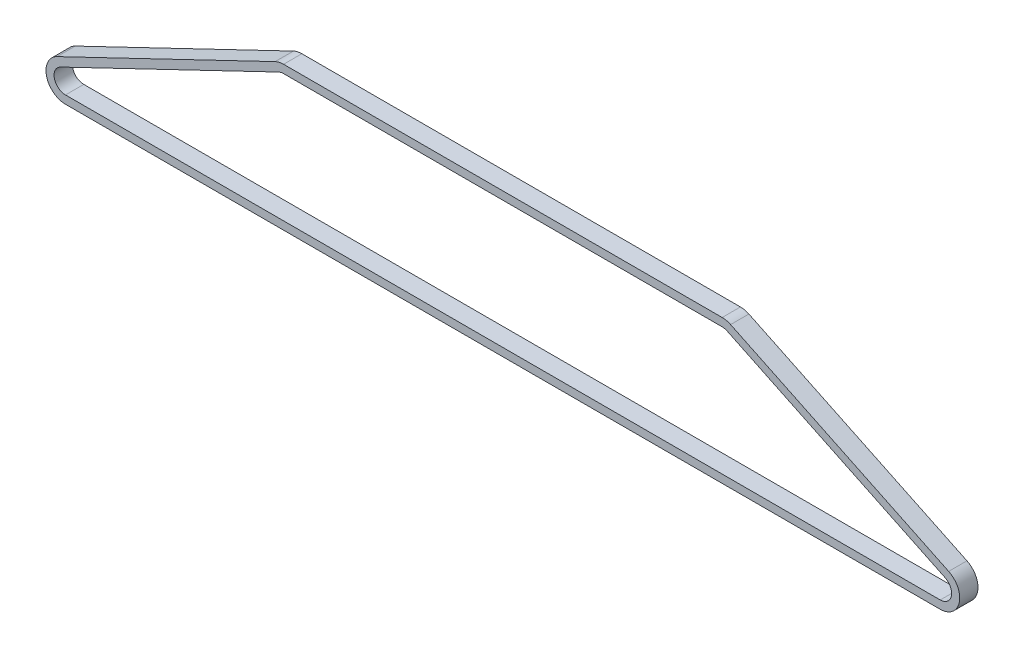
SolidWorks part; units mm, degrees
material "Rubber"
ref_plane "Front Plane" through (0, 0, 0) normal (0, 0, 1) x (1, 0, 0)
ref_plane "Top Plane" through (0, 0, 0) normal (0, 1, 0) x (1, 0, 0)
ref_plane "Right Plane" through (0, 0, 0) normal (1, 0, 0) x (0, 0, -1)
sketch "Sketch1" plane through (0, 0, 0) normal (0, 0, 1) x (1, 0, 0)
  line L0 (-72, 0) -> (0, 0) construction
  line L1 (-72, 1.872) -> (0, 1.872)
  line L2 (-107.8, -17.1867) -> (-72, 0) construction
  line L3 (-108.6102, -15.4991) -> (-72.8102, 1.6876)
  line L5 (-71.5739, -1.872) -> (-0.4261, -1.872)
  line L6 (-107.8, -17.1867) -> (35.8, -17.1867) construction
  line L8 (-107.8, -19.0587) -> (35.8, -19.0587)
  line L9 (-99.5752, -15.3147) -> (-71.5739, -1.872)
  line L10 (-99.5752, -15.3147) -> (27.5752, -15.3147)
  line L11 (0, 0) -> (35.8, -17.1867) construction
  line L12 (0.8102, 1.6876) -> (36.6102, -15.4991)
  line L13 (-0.4261, -1.872) -> (27.5752, -15.3147)
  line L14 (-72, 0) -> (0, 0) construction
  line L15 (-72, 3.2) -> (0, 3.2)
  line L16 (-71.2717, -3.2) -> (-0.7283, -3.2)
  line L17 (35.8, -17.1867) -> (0, 0) construction
  line L18 (21.7405, -13.9867) -> (-0.7283, -3.2)
  line L19 (37.1849, -14.3019) -> (1.3849, 2.8848)
  line L20 (35.8, -17.1867) -> (-107.8, -17.1867) construction
  line L21 (35.8, -20.3867) -> (-107.8, -20.3867)
  line L22 (33.4598, -13.9867) -> (24.8089, -13.9867)
  line L23 (-107.8, -17.1867) -> (-72, 0) construction
  line L24 (-109.1849, -14.3019) -> (-73.3849, 2.8848)
  line L25 (-93.7405, -13.9867) -> (-71.2717, -3.2)
  line L26 (21.7405, -13.9867) -> (-93.7405, -13.9867)
  circle A0 centre (35.8, -17.1867) radius 1.872 construction
  arc A1 (-72, 3.2) -> (-73.3849, 2.8848) centre (-72, 0) ccw
  arc A2 (35.8, -19.0587) -> (36.6102, -15.4991) centre (35.8, -17.1867) ccw
  circle A4 centre (-72, 0) radius 9.25 construction
  circle A6 centre (-72, 0) radius 9.25 construction
  circle A8 centre (-107.8, -17.1867) radius 1.872 construction
  arc A9 (-108.6102, -15.4991) -> (-107.8, -19.0587) centre (-107.8, -17.1867) ccw
  circle A10 centre (-107.8, -17.1867) radius 3.2 construction
  arc A11 (-109.1849, -14.3019) -> (-107.8, -20.3867) centre (-107.8, -17.1867) ccw
  arc A12 (-108.6102, -15.4991) -> (-107.8, -19.0587) centre (-107.8, -17.1867) ccw
  arc A14 (-72, 1.872) -> (-72.8102, 1.6876) centre (-72, 0) ccw
  arc A16 (-108.6102, -15.4991) -> (-107.8, -19.0587) centre (-107.8, -17.1867) ccw
  arc A17 (35.8, -19.0587) -> (36.6102, -15.4991) centre (35.8, -17.1867) ccw
  arc A18 (-72, 1.872) -> (-72.8102, 1.6876) centre (-72, 0) ccw
  arc A19 (0.8102, 1.6876) -> (0, 1.872) centre (0, 0) ccw
  arc A20 (35.8, -19.0587) -> (36.6102, -15.4991) centre (35.8, -17.1867) ccw
  arc A21 (0.8102, 1.6876) -> (0, 1.872) centre (0, 0) ccw
  arc A22 (1.3849, 2.8848) -> (0, 3.2) centre (0, 0) ccw
  arc A23 (35.8, -20.3867) -> (37.1849, -14.3019) centre (35.8, -17.1867) ccw
  arc A24 (1.3849, 2.8848) -> (0, 3.2) centre (0, 0) ccw
  arc A25 (35.8, -20.3867) -> (37.1849, -14.3019) centre (35.8, -17.1867) ccw
  arc A26 (-109.1849, -14.3019) -> (-107.8, -20.3867) centre (-107.8, -17.1867) ccw
  arc A27 (-109.1849, -14.3019) -> (-107.8, -20.3867) centre (-107.8, -17.1867) ccw
  arc A28 (-72.0041, -3.2) -> (-72, -3.2) centre (-72, 0) ccw
  arc A29 (-72, 3.2) -> (-73.3849, 2.8848) centre (-72, 0) ccw
  arc A30 (-72.0041, -3.2) -> (-72, -3.2) centre (-72, 0) ccw
  point P4 (-36, 0)
  point P7 (-36, 0)
  point P13 (17.9, -8.5934)
  point P20 (-36, -17.1867)
  point P22 (-89.9, -8.5934)
  point P37 (17.9, -8.5934)
  point P44 (-36, -17.1867)
  point P51 (-89.9, -8.5934)
extrude "Boss-Extrude1" add sketch "Sketch1" along normal blind 3 contours L21 A23 L19 A22 L15 A1 L24 A11 A19 L12 A2 L8 A9 L3 A14 L1
